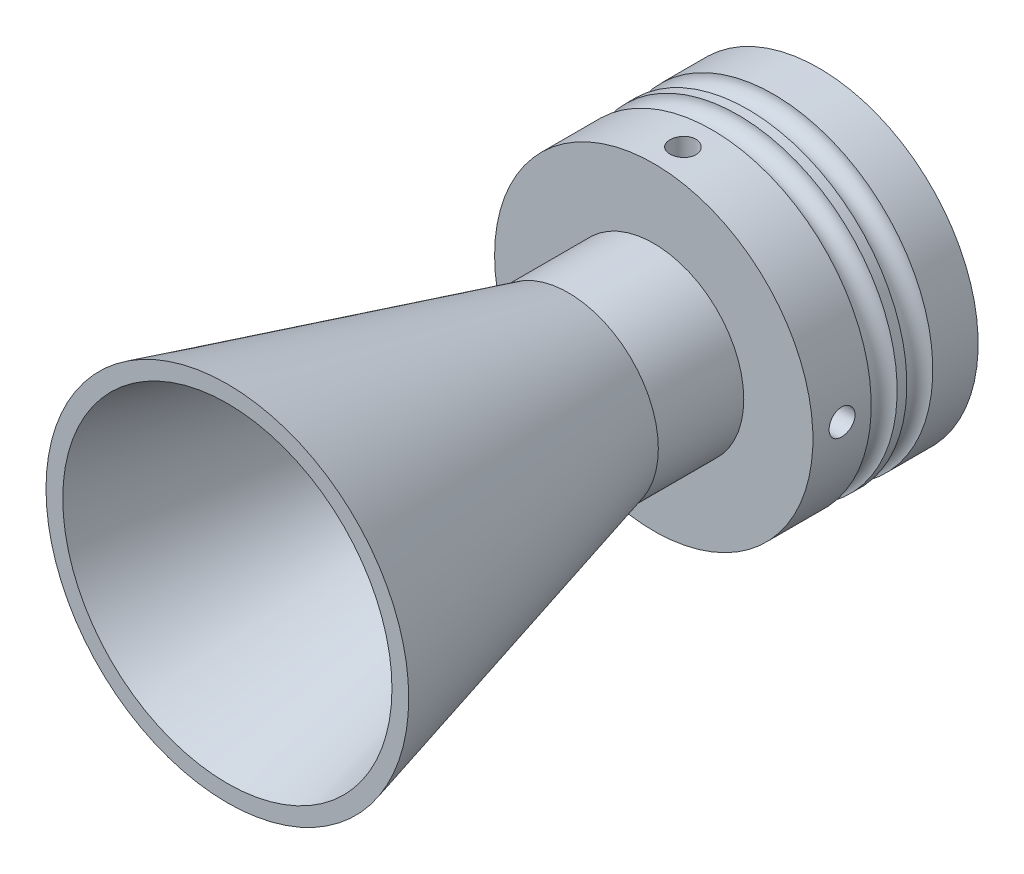
SolidWorks part; units mm, degrees
material "Stainless Steel (ferritic)"
ref_plane "Front Plane" through (0, 0, 0) normal (0, 0, 1) x (1, 0, 0)
ref_plane "Top Plane" through (0, 0, 0) normal (0, 1, 0) x (1, 0, 0)
ref_plane "Right Plane" through (0, 0, 0) normal (1, 0, 0) x (0, 0, -1)
sketch "Sketch1" plane through (0, 0, 0) normal (0, 1, 0) x (1, 0, 0)
  line L0 (24.5618, 27.1444) -> (8.89, 0)
  line L1 (8.89, 0) -> (8.89, -2.54)
  line L2 (8.89, -2.54) -> (25.4, -64.1562)
  line L3 (0, 75.3084) -> (0, -95.0864) construction
  line L6 (13.89, -11.541) -> (27.9882, -64.1562)
  line L8 (26.7269, 25.8944) -> (11.39, -0.6699) construction
  line L9 (25.4, -64.1562) -> (27.9882, -64.1562)
  line L10 (11.39, -2.2109) -> (27.8148, -63.5091) construction
  line L12 (24.5618, 1.6444) -> (24.5618, 10.6444)
  line L13 (24.5618, 20.1444) -> (24.5618, 27.1444)
  line L14 (11.39, -0.6699) -> (11.39, -2.2109) construction
  line L16 (13.89, 1.6444) -> (24.5618, 1.6444)
  line L17 (24.5618, 16.1444) -> (24.5618, 14.6444)
  line L18 (13.89, 1.6444) -> (13.89, -11.541)
  arc A2 (24.5618, 20.1444) -> (24.5618, 16.1444) centre (24.5618, 18.1444) ccw
  arc A3 (24.5618, 14.6444) -> (24.5618, 10.6444) centre (24.5618, 12.6444) ccw
  point P9 (8.89, -1.27)
  dimension "D8" = 4
  dimension "D9" = 7
  dimension "D11" = 1.5
  dimension "D12" = 4
  dimension "D1" = 15
  dimension "D2" = 2.54
  dimension "D3" = 30
  dimension "D4" = 8.89
  dimension "D5" = 25.4
  dimension "D6" = 24.5618
  dimension "D10" = 25.5
  dimension "D13" = 5
  dimension "D7" = 2.5
revolve "Revolve2" add sketch "Sketch1" angle 360 about L3
ref_plane "Plane3" through (0, 0, -1.6444) normal (0, 0, 1) x (1, 0, 0)
ref_plane "Plane2" through (0, 0, -6.1444) normal (0, 0, 1) x (1, 0, 0)
hole_wizard "Ø4.0mm Dowel Hole1" positions "3DSketch1" profile "Sketch2" hole size "Ø4.0" standard "ISO"
sketch3d "3DSketch1"
  line L0 (0, 24.5618, -6.1444) -> (0, -24.5618, -6.1444)
  line L2 (-24.5618, 0, -6.1444) -> (24.5618, 0, -6.1444)
  point P0 (0, 0, 0)
  point P3 (0, 0, 0)
  point P5 (0, 24.5618, -6.1444)
  point P7 (24.5618, 0, -6.1444)
  point P9 (0, -24.5618, -6.1444)
  point P11 (-24.5618, 0, -6.1444)
  dimension "D1" = 0
sketch "Sketch2" plane through (-24.5618, 0, -6.1444) normal (0, 1, 0) x (0, 0, 1)
  line L0 (0, 0) -> (0, 6.2017)
  line L1 (0, 6.2017) -> (2, 5)
  line L2 (2, 5) -> (2, 0)
  line L5 (2, 0) -> (0, 0)
  line L10 (0, 6.2017) -> (-2, 5) construction
  line L11 (0, -6.35) -> (0, 107.95) construction
  dimension "Hole Dia." = 4
  dimension "Hole Depth" = 5
  dimension "Drill Angle" = 118
ref_plane "Plane4" through (0, 0, -27.1444) normal (0, 0, 1) x (1, 0, 0)
